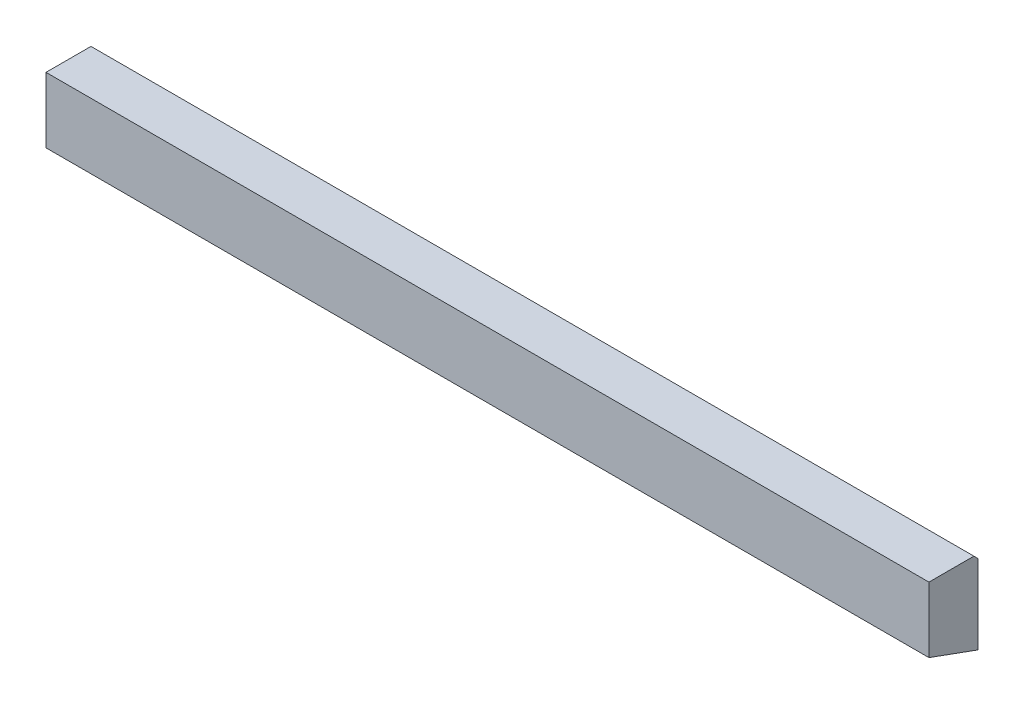
SolidWorks part; units mm, degrees
ref_plane "前视基准面" through (0, 0, 0) normal (0, 0, 1) x (1, 0, 0)
ref_plane "上视基准面" through (0, 0, 0) normal (0, 1, 0) x (1, 0, 0)
ref_plane "右视基准面" through (0, 0, 0) normal (1, 0, 0) x (0, 0, -1)
sketch "草图1" plane through (0, 0, 0) normal (1, 0, 0) x (0, 0, -1)
  line L0 (0, 8) -> (0, 0)
  line L1 (0, 0) -> (6, -2.1838)
  line L2 (6, -2.1838) -> (6, 8)
  line L3 (6, 8) -> (0, 8)
  dimension "D1" = 8
  dimension "D2" = 6
  dimension "D3" = 110
extrude "凸台-拉伸1" add sketch "草图1" along normal blind 108 contours L2 L3 L0 L1
chamfer "倒角1" distance 0.5 angle 45 1 edges at (54, 8, -6)
